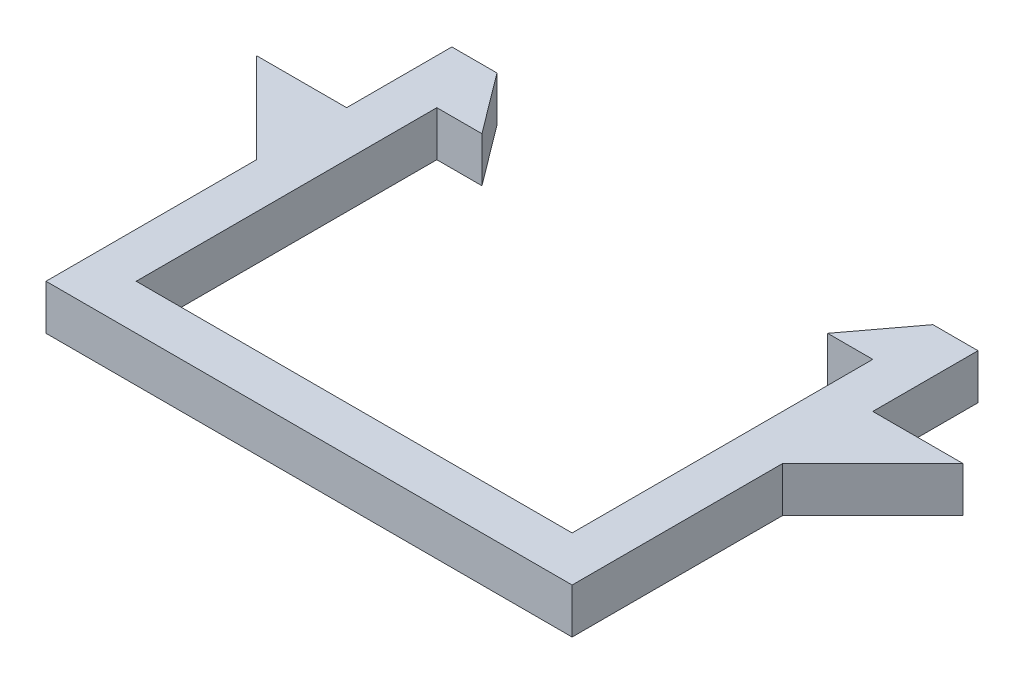
SolidWorks part; units mm, degrees
ref_plane "Front Plane" through (0, 0, 0) normal (0, 0, 1) x (1, 0, 0)
ref_plane "Top Plane" through (0, 0, 0) normal (0, 1, 0) x (1, 0, 0)
ref_plane "Right Plane" through (0, 0, 0) normal (1, 0, 0) x (0, 0, -1)
sketch "Sketch1" plane through (0, 0, 0) normal (0, 1, 0) x (1, 0, 0)
  line L0 (-189.2477, 0) -> (9273.1362, 0) construction
  line L1 (0, -189.2477) -> (0, 9273.1362) construction
  line L2 (17.5, 0) -> (-17.5, 0)
  line L3 (-17.5, 0) -> (-17.5, 14)
  line L4 (-17.5, 14) -> (-23.5, 20)
  line L5 (-23.5, 20) -> (-17.5, 20)
  line L6 (-17.5, 20) -> (-17.5, 27)
  line L7 (-17.5, 27) -> (-14.5, 27)
  line L8 (-14.5, 27) -> (-11.5, 23)
  line L9 (-11.5, 23) -> (-14.5, 23)
  line L10 (-14.5, 23) -> (-14.5, 3)
  line L11 (-14.5, 3) -> (14.5, 3)
  line L12 (14.5, 23) -> (14.5, 3)
  line L13 (11.5, 23) -> (14.5, 23)
  line L14 (14.5, 27) -> (11.5, 23)
  line L15 (17.5, 27) -> (14.5, 27)
  line L16 (17.5, 20) -> (17.5, 27)
  line L17 (23.5, 20) -> (17.5, 20)
  line L18 (17.5, 14) -> (23.5, 20)
  line L19 (17.5, 0) -> (17.5, 14)
  point P4 (-15.0864, 27)
  point P13 (-13, 23)
  point P17 (-9.6661, 27)
  point P19 (0, 3)
  point P27 (0, 0)
  point P28 (-14.5, 27)
  point P29 (0, 0)
  dimension "D1" = 3
  dimension "D2" = 3
  dimension "D3" = 14
  dimension "D4" = 3
  dimension "D5" = 4
  dimension "D6" = 7
  dimension "D7" = 6
  dimension "D8" = 135
  dimension "D9" = 27
  dimension "D10" = 47
extrude "Boss-Extrude1" add sketch "Sketch1" along normal blind 3
